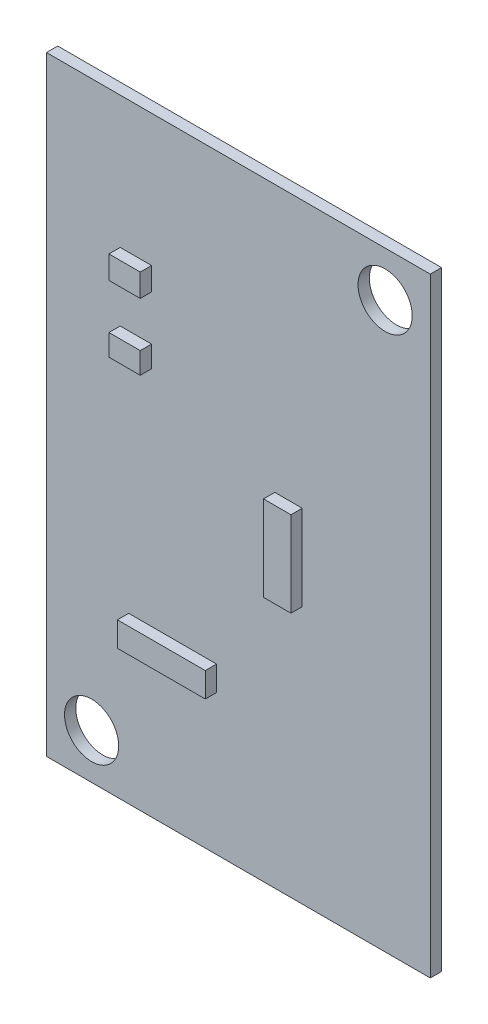
SolidWorks part; units mm, degrees
ref_plane "Alzado" through (0, 0, 0) normal (0, 0, 1) x (1, 0, 0)
ref_plane "Planta" through (0, 0, 0) normal (0, 1, 0) x (1, 0, 0)
ref_plane "Vista lateral" through (0, 0, 0) normal (1, 0, 0) x (0, 0, -1)
sketch "Croquis1" plane through (0, 0, 0) normal (0, 0, 1) x (1, 0, 0)
  line L1 (0, 0) -> (17, 0)
  line L2 (0, 0) -> (0, 27)
  line L3 (0, 27) -> (17, 27)
  line L4 (17, 0) -> (17, 27)
  dimension "D1" = 17
  dimension "D2" = 27
extrude "Saliente-Extruir1" add sketch "Croquis1" along normal blind 0.5
sketch "Croquis2" plane through (0, 0, 0.5) normal (0, 0, 1) x (1, 0, 0)
  line L0 (0, 27) -> (0, 0) construction
  line L1 (0, 0) -> (17, 0) construction
  line L2 (17, 27) -> (0, 27) construction
  line L3 (17, 0) -> (17, 27) construction
  circle A0 centre (2, 2) radius 1.2
  circle A1 centre (15, 25) radius 1.2
  dimension "D1" = 2.4
  dimension "D2" = 2
  dimension "D3" = 2
  dimension "D4" = 2
  dimension "D5" = 2
extrude "Cortar-Extruir1" cut sketch "Croquis2" against normal up to surface (0.5 mm away) up to face at (8.5, 13.5, 0)
sketch "Croquis3" plane through (0, 0, 0.5) normal (0, 0, 1) x (1, 0, 0)
  line L1 (3.2671, 21.1574) -> (4.6541, 21.1574)
  line L2 (3.2671, 21.1574) -> (3.2671, 20.1429)
  line L3 (3.2671, 20.1429) -> (4.6541, 20.1429)
  line L4 (4.6541, 21.1574) -> (4.6541, 20.1429)
  line L5 (3.2671, 18.1442) -> (4.6541, 18.1442)
  line L6 (3.2671, 18.1442) -> (3.2671, 17.1967)
  line L7 (3.2671, 17.1967) -> (4.6541, 17.1967)
  line L8 (4.6541, 18.1442) -> (4.6541, 17.1967)
  line L9 (10.1133, 15.1846) -> (11.3299, 15.1846)
  line L10 (10.1133, 15.1846) -> (10.1133, 11.4079)
  line L11 (10.1133, 11.4079) -> (11.3299, 11.4079)
  line L12 (11.3299, 15.1846) -> (11.3299, 11.4079)
  line L13 (3.6424, 7.3104) -> (7.5348, 7.3104)
  line L14 (3.6424, 7.3104) -> (3.6424, 6.2185)
  line L15 (3.6424, 6.2185) -> (7.5348, 6.2185)
  line L16 (7.5348, 7.3104) -> (7.5348, 6.2185)
extrude "Saliente-Extruir2" add sketch "Croquis3" along normal blind 0.5
